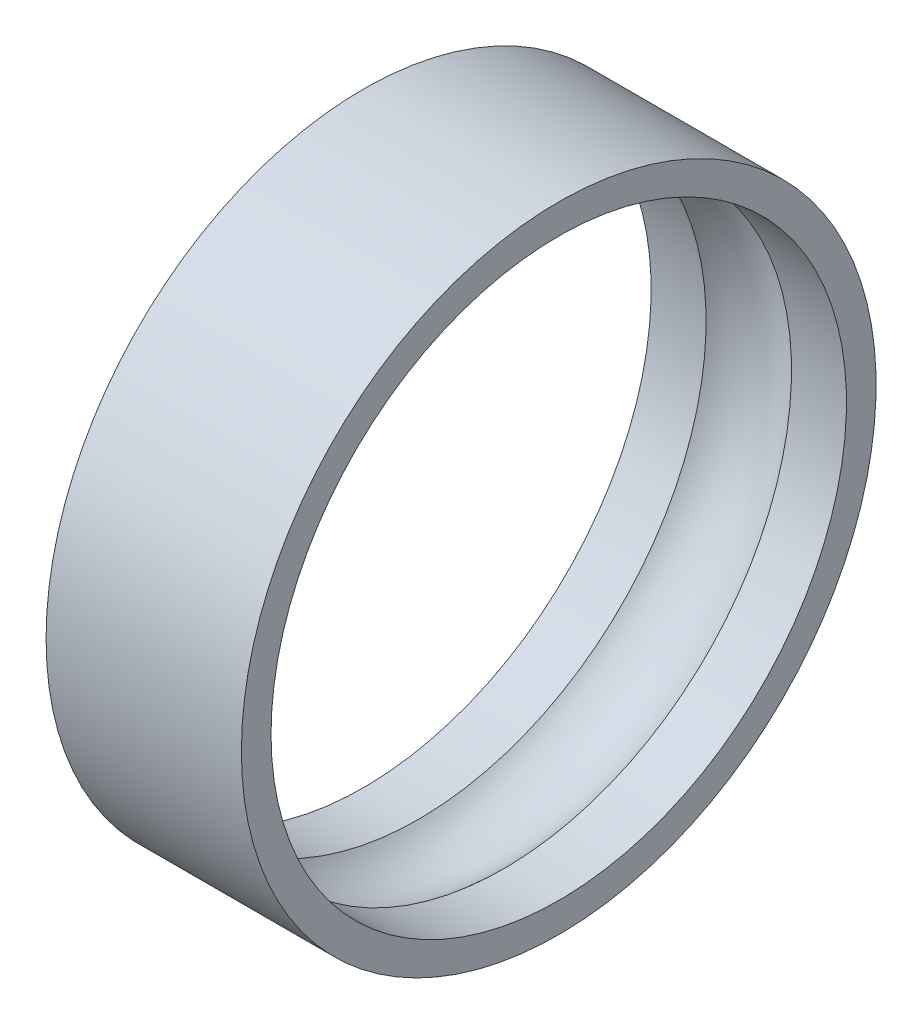
SolidWorks part; units mm, degrees
ref_plane "Plan de face" through (0, 0, 0) normal (0, 0, 1) x (1, 0, 0)
ref_plane "Plan de dessus" through (0, 0, 0) normal (0, 1, 0) x (1, 0, 0)
ref_plane "Plan de droite" through (0, 0, 0) normal (1, 0, 0) x (0, 0, -1)
sketch "Esquisse1" plane through (0, 0, 0) normal (0, 0, 1) x (1, 0, 0)
  line L0 (-1.75, -1.7854) -> (1.75, -1.7854) construction
  line L1 (-1.75, -1.7854) -> (-4, -1.7854)
  line L2 (-4, -1.7854) -> (-4, -3)
  line L3 (-4, -3) -> (4, -3)
  line L4 (4, -3) -> (4, -1.7854)
  line L5 (4, -1.7854) -> (1.75, -1.7854)
  line L6 (-1011.1003, 10) -> (48988.8997, 10) construction
  circle A0 centre (0, 0) radius 2.5 construction
  arc A1 (-1.75, -1.7854) -> (1.75, -1.7854) centre (0, 0) ccw
  dimension "D4" = 5
  dimension "D1" = 8
  dimension "D2" = 10
  dimension "D3" = 13
  dimension "D6" = 3.5
revolve "Révolution1" add sketch "Esquisse1" angle 360 about L6
